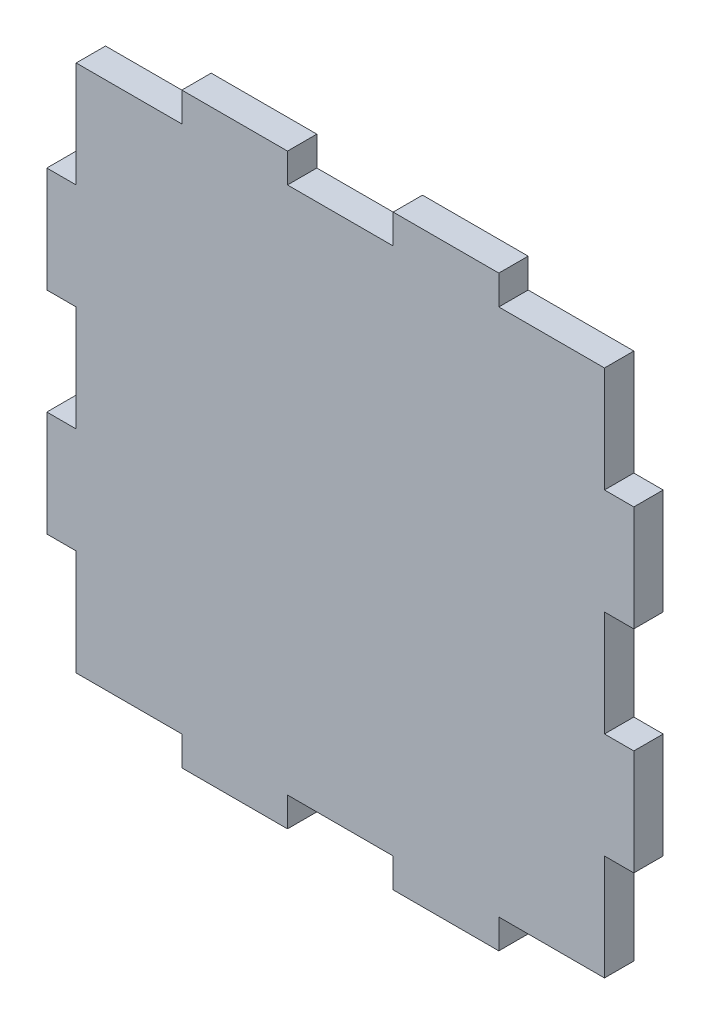
SolidWorks part; units mm, degrees
ref_plane "Front Plane" through (0, 0, 0) normal (0, 0, 1) x (1, 0, 0)
ref_plane "Top Plane" through (0, 0, 0) normal (0, 1, 0) x (1, 0, 0)
ref_plane "Right Plane" through (0, 0, 0) normal (1, 0, 0) x (0, 0, -1)
sketch "Esquisse1" plane through (0, 0, 0) normal (0, 0, 1) x (1, 0, 0)
  line L1 (0, 0) -> (-90, 0)
  line L2 (0, 0) -> (0, -90)
  line L3 (0, -90) -> (-90, -90)
  line L4 (-90, 0) -> (-90, -90)
  line L5 (-45, -90) -> (-45, 0) construction
  line L6 (0, -45) -> (-90, -45) construction
  point P4 (0, 0)
  point P72 (-45, -45)
  dimension "D1" = 90
extrude "Boss.-Extru.1" add sketch "Esquisse1" along normal blind 5
sketch "Esquisse2" plane through (0, 0, 0) normal (0, 0, -1) x (-1, 0, 0)
  line L0 (0, -90) -> (0, 0) construction
  line L1 (-5, -18) -> (0, -18)
  line L2 (-5, -18) -> (-5, -36)
  line L3 (-5, -36) -> (0, -36)
  line L4 (0, -18) -> (0, -36)
  line L5 (-2.5, -36) -> (-2.5, -18) construction
  line L6 (-5, -27) -> (0, -27) construction
  line L7 (-5, -36) -> (0, -36) construction
  line L8 (-5, -72) -> (0, -72) construction
  line L9 (-5, -54) -> (0, -54)
  line L10 (-5, -54) -> (-5, -72)
  line L11 (-5, -72) -> (0, -72)
  line L12 (0, -54) -> (0, -72)
  line L13 (-2.5, -72) -> (-2.5, -54) construction
  line L14 (-5, -63) -> (0, -63) construction
  line L15 (45, 0) -> (45, -90) construction
  line L16 (0, 0) -> (90, 0) construction
  line L17 (90, -90) -> (0, -90) construction
  line L18 (95, -63) -> (90, -63) construction
  line L19 (92.5, -72) -> (92.5, -54) construction
  line L20 (95, -27) -> (90, -27) construction
  line L21 (92.5, -36) -> (92.5, -18) construction
  line L22 (90, -54) -> (90, -72)
  line L23 (95, -72) -> (90, -72)
  line L24 (95, -54) -> (95, -72)
  line L25 (95, -54) -> (90, -54)
  line L26 (90, -18) -> (90, -36)
  line L27 (95, -36) -> (90, -36)
  line L28 (95, -18) -> (95, -36)
  line L29 (95, -18) -> (90, -18)
  point P40 (92.5, -63)
  point P41 (92.5, -27)
  point P136 (-2.5, -27)
  point P138 (-2.5, -63)
extrude "Boss.-Extru.2" add sketch "Esquisse2" against normal blind 5
sketch "Esquisse3" plane through (0, 0, 0) normal (0, 0, -1) x (-1, 0, 0)
  line L0 (95, 5) -> (72, 5) construction
  line L1 (18, 5) -> (36, 5)
  line L2 (18, 5) -> (18, 0)
  line L3 (18, 0) -> (36, 0)
  line L4 (36, 5) -> (36, 0)
  line L5 (27, 0) -> (27, 5) construction
  line L6 (18, 2.5) -> (36, 2.5) construction
  line L7 (0, 0) -> (90, 0) construction
  line L8 (0, -18) -> (0, 0) construction
  line L9 (54, 5) -> (72, 5)
  line L10 (54, 5) -> (54, 0)
  line L11 (54, 0) -> (72, 0)
  line L12 (72, 5) -> (72, 0)
  line L13 (63, 0) -> (63, 5) construction
  line L14 (54, 2.5) -> (72, 2.5) construction
  line L15 (0, -45) -> (90, -45) construction
  line L16 (0, -54) -> (0, -36) construction
  line L17 (90, -36) -> (90, -54) construction
  line L18 (54, -92.5) -> (72, -92.5) construction
  line L19 (63, -90) -> (63, -95) construction
  line L20 (18, -92.5) -> (36, -92.5) construction
  line L21 (27, -90) -> (27, -95) construction
  line L22 (72, -95) -> (72, -90)
  line L23 (54, -90) -> (72, -90)
  line L24 (54, -95) -> (54, -90)
  line L25 (54, -95) -> (72, -95)
  line L26 (36, -95) -> (36, -90)
  line L27 (18, -90) -> (36, -90)
  line L28 (18, -95) -> (18, -90)
  line L29 (18, -95) -> (36, -95)
  point P40 (63, -92.5)
  point P41 (27, -92.5)
  point P100 (27, 2.5)
  point P109 (63, 2.5)
  dimension "D1" = 18
  dimension "D2" = 18
  dimension "D3" = 18
  dimension "D4" = 18
extrude "Boss.-Extru.3" add sketch "Esquisse3" against normal blind 5
